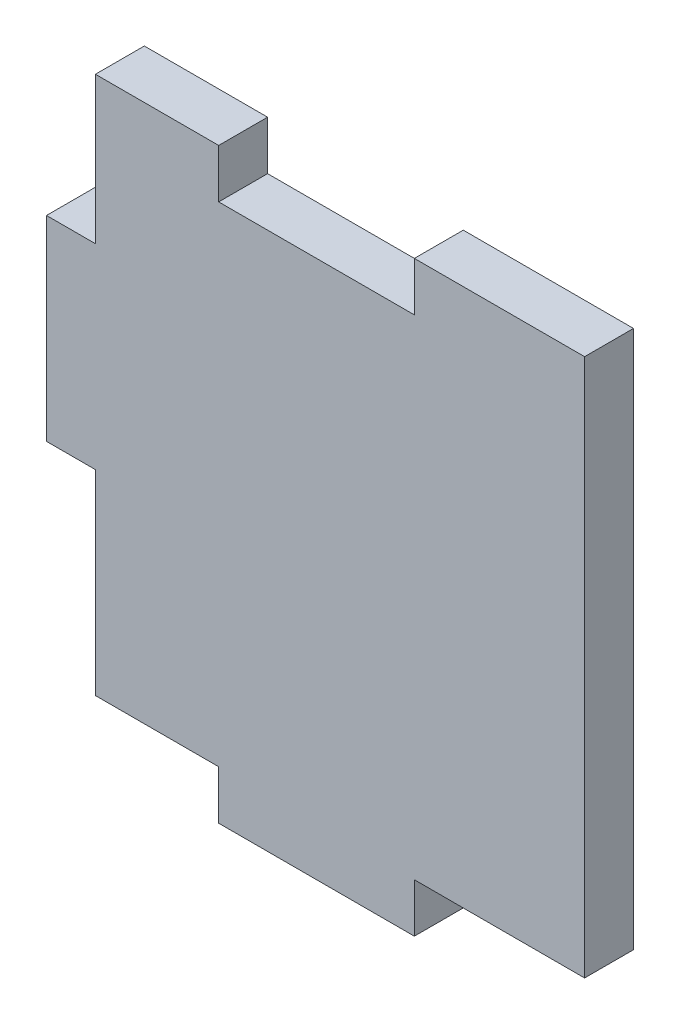
SolidWorks part; units mm, degrees
ref_plane "Front Plane" through (0, 0, 0) normal (0, 0, 1) x (1, 0, 0)
ref_plane "Top Plane" through (0, 0, 0) normal (0, 1, 0) x (1, 0, 0)
ref_plane "Right Plane" through (0, 0, 0) normal (1, 0, 0) x (0, 0, -1)
sketch "Sketch1" plane through (0, 0, 0) normal (0, 0, 1) x (1, 0, 0)
  line L0 (0, 6.35) -> (16.002, 6.35)
  line L1 (16.002, 6.35) -> (16.002, 0)
  line L2 (16.002, 0) -> (41.402, 0)
  line L3 (41.402, 0) -> (41.402, 6.35)
  line L4 (41.402, 6.35) -> (63.5, 6.35)
  line L6 (63.5, 76.2) -> (41.402, 76.2)
  line L7 (0, 76.2) -> (0, 57.15)
  line L8 (0, 6.35) -> (0, 0) construction
  line L9 (0, 0) -> (16.002, 0) construction
  line L10 (28.702, 0) -> (28.702, 76.2) construction
  line L11 (0, 57.15) -> (-6.35, 57.15)
  line L12 (-6.35, 57.15) -> (-6.35, 31.75)
  line L13 (-6.35, 31.75) -> (0, 31.75)
  line L14 (0, 31.75) -> (0, 6.35)
  line L15 (16.002, 76.2) -> (16.002, 69.85)
  line L16 (16.002, 69.85) -> (41.402, 69.85)
  line L17 (41.402, 69.85) -> (41.402, 76.2)
  line L18 (16.002, 76.2) -> (0, 76.2)
  line L19 (16.002, 76.2) -> (41.402, 76.2) construction
  line L23 (63.5, 6.35) -> (63.5, 76.2)
  point P18 (28.702, 69.85)
  dimension "D1" = 25.4
  dimension "D2" = 6.35
  dimension "D3" = 63.5
  dimension "D4" = 69.85
  dimension "D5" = 6.35
  dimension "D6" = 25.4
  dimension "D7" = 25.4
  dimension "D8" = 25.4
  dimension "D9" = 6.35
  dimension "D10" = 28.702
extrude "Extrude1" add sketch "Sketch1" along normal blind 6.35
